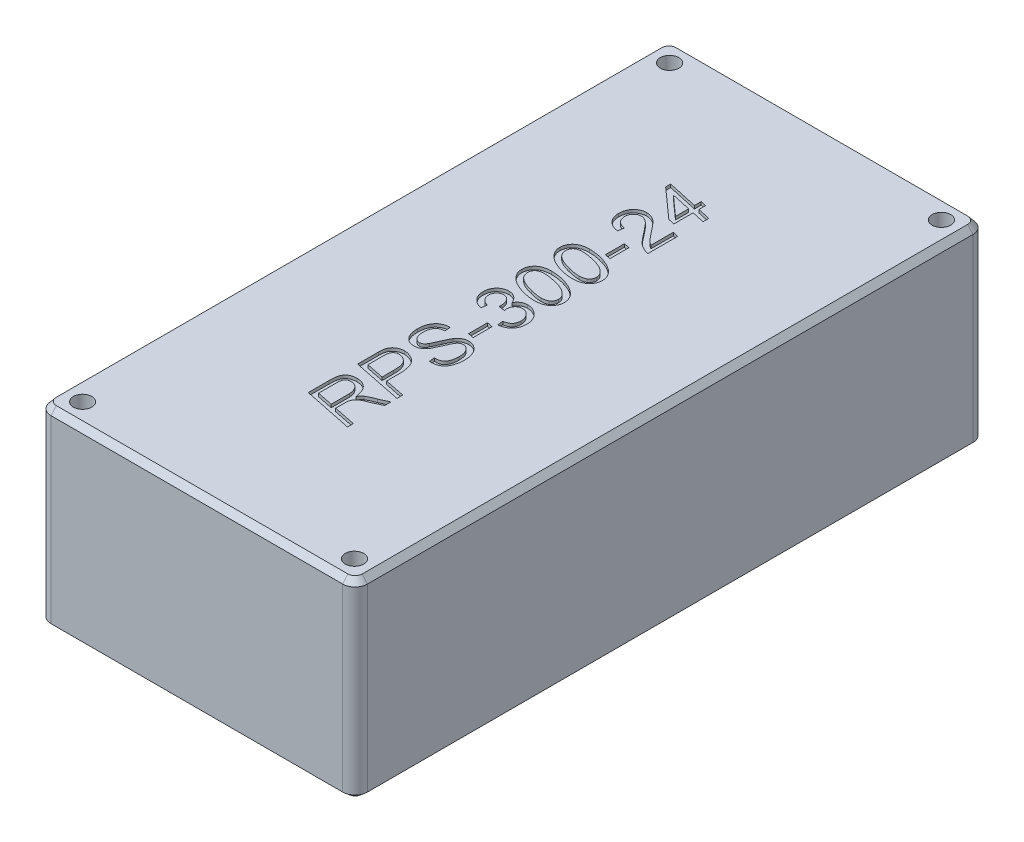
SolidWorks part; units mm, degrees
ref_plane "Спереди" through (0, 0, 0) normal (0, 0, 1) x (1, 0, 0)
ref_plane "Сверху" through (0, 0, 0) normal (0, 1, 0) x (1, 0, 0)
ref_plane "Справа" through (0, 0, 0) normal (1, 0, 0) x (0, 0, -1)
sketch "Эскиз1" plane through (0, 0, 0) normal (0, 1, 0) x (1, 0, 0)
  line L1 (-25.6, 51) -> (25.6, 51)
  line L2 (-25.6, 51) -> (-25.6, -51)
  line L3 (-25.6, -51) -> (25.6, -51)
  line L4 (25.6, 51) -> (25.6, -51)
  line L5 (-25.6, 51) -> (25.6, -51) construction
  line L6 (-25.6, -51) -> (25.6, 51) construction
  line L7 (22, -47.5) -> (-22, -47.5) construction
  line L8 (22, -47.5) -> (22, 47.5) construction
  line L9 (22, 47.5) -> (-22, 47.5) construction
  line L10 (-22, -47.5) -> (-22, 47.5) construction
  line L11 (22, -47.5) -> (-22, 47.5) construction
  line L12 (22, 47.5) -> (-22, -47.5) construction
  circle A0 centre (-22, 47.5) radius 1.5
  circle A1 centre (22, 47.5) radius 1.5
  circle A2 centre (-22, -47.5) radius 1.5
  circle A3 centre (22, -47.5) radius 1.5
  point P0 (0, 0)
  point P6 (0, 0)
  dimension "D5" = 3
  dimension "D1" = 102
  dimension "D2" = 51.2
  dimension "D3" = 95
  dimension "D4" = 44
extrude "Бобышка-Вытянуть1" add sketch "Эскиз1" along normal blind 31
sketch "Эскиз2" plane through (9.7115, 0, 7.4903) normal (0, 1, 0) x (0, 0, -1)
  text T0 "RPS-300-24" font "Arial" height 8
extrude "Вырез-Вытянуть1" cut sketch "Эскиз2" against normal blind 0.5 from surface at 31 starting at face at (-22, 31, 49)
fillet "Скругление1" radius 2 4 edges at (-25.6, 15.5, -51) (25.6, 15.5, -51) (25.6, 15.5, 51) (-25.6, 15.5, 51)
chamfer "Фаска1" distance 1 angle 40 16 edges at (-25.6, 31, 0) (-25.0142, 31, 50.4142) (-25.0142, 31, -50.4142) (0, 31, 51) (0, 31, -51) (25.0142, 31, 50.4142) (25.0142, 31, -50.4142) (25.6, 31, 0) (-25.6, 0, 0) (-25.0142, 0, 50.4142) (-25.0142, 0, -50.4142) (0, 0, 51) (0, 0, -51) (25.0142, 0, 50.4142) (25.0142, 0, -50.4142) (25.6, 0, 0)
